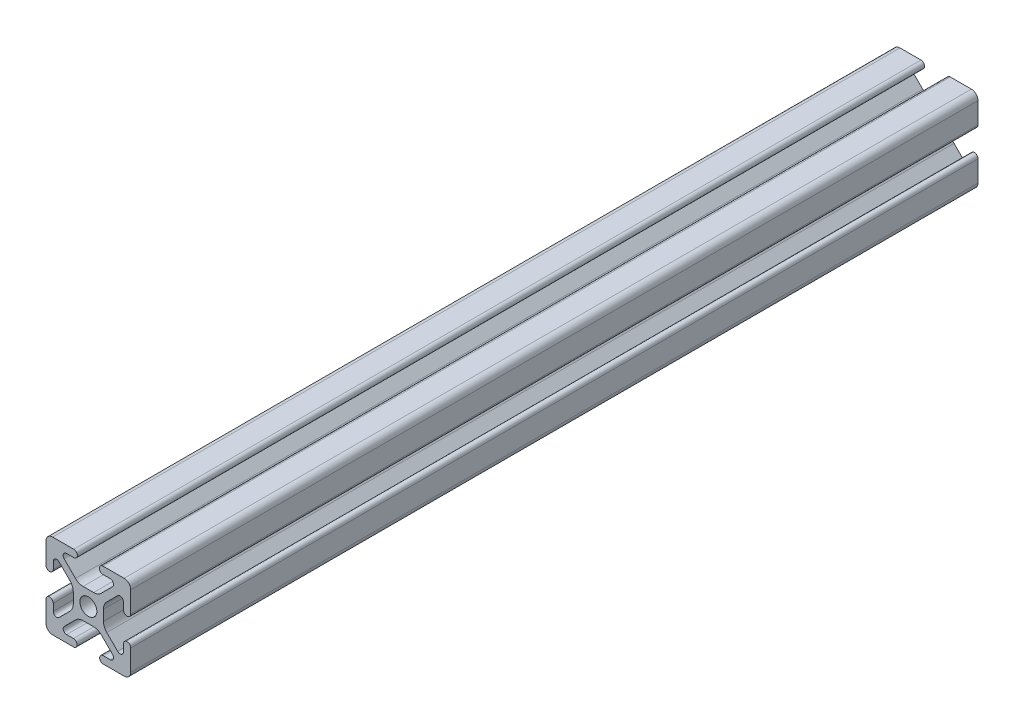
SolidWorks part; units mm, degrees
ref_plane "Front Plane" through (0, 0, 0) normal (0, 0, 1) x (1, 0, 0)
ref_plane "Top Plane" through (0, 0, 0) normal (0, 1, 0) x (1, 0, 0)
ref_plane "Right Plane" through (0, 0, 0) normal (1, 0, 0) x (0, 0, -1)
ref_plane "Plane1" through (0, 0, -25) normal (0, 0, -1) x (-1, 0, 0)
sketch "Sketch1" plane through (0, 0, -25) normal (0, 0, -1) x (-1, 0, 0)
  line L0 (12.5, 4.32) -> (12.5, 10.5371)
  line L1 (10.5371, 12.5) -> (4.32, 12.5)
  line L2 (4.32, 10.36) -> (6.42, 10.36)
  line L3 (7.1337, 8.6353) -> (3.7953, 5.3018)
  line L4 (1.5554, 4.375) -> (-1.5554, 4.375)
  line L5 (-3.7953, 5.3018) -> (-7.1337, 8.6353)
  line L6 (-6.42, 10.36) -> (-4.32, 10.36)
  line L7 (-4.32, 12.5) -> (-10.5371, 12.5)
  line L8 (-12.5, 10.5371) -> (-12.5, 4.32)
  line L9 (-10.36, 4.32) -> (-10.36, 6.3969)
  line L10 (-8.6363, 7.1116) -> (-5.4322, 3.9121)
  line L11 (-4.455, 1.5554) -> (-4.455, -1.5554)
  line L12 (-5.4322, -3.9121) -> (-8.6363, -7.1116)
  line L13 (-10.36, -6.3969) -> (-10.36, -4.32)
  line L14 (-12.5, -4.32) -> (-12.5, -10.5371)
  line L15 (-10.5371, -12.5) -> (-4.3879, -12.5)
  line L16 (-4.3879, -10.36) -> (-6.42, -10.36)
  line L17 (-7.1337, -8.6353) -> (-3.7953, -5.3018)
  line L18 (-1.5554, -4.375) -> (1.5554, -4.375)
  line L19 (3.7953, -5.3018) -> (7.1337, -8.6353)
  line L20 (6.42, -10.36) -> (4.3879, -10.36)
  line L21 (4.3879, -12.5) -> (10.5371, -12.5)
  line L22 (12.5, -10.5371) -> (12.5, -4.32)
  line L23 (10.36, -4.32) -> (10.36, -6.3969)
  line L24 (8.6363, -7.1116) -> (5.4322, -3.9121)
  line L25 (4.455, -1.5554) -> (4.455, 1.5554)
  line L26 (5.4322, 3.9121) -> (8.6363, 7.1116)
  line L27 (10.36, 6.3969) -> (10.36, 4.32)
  circle A0 centre (0, 0) radius 2.5
  arc A1 (12.5, 10.5371) -> (10.5371, 12.5) centre (10.5371, 10.5371) ccw
  arc A2 (4.32, 12.5) -> (4.32, 10.36) centre (4.32, 11.43) ccw
  arc A3 (6.42, 10.36) -> (7.1337, 8.6353) centre (6.42, 9.35) cw
  arc A4 (3.7953, 5.3018) -> (1.5554, 4.375) centre (1.5554, 7.545) cw
  arc A5 (-1.5554, 4.375) -> (-3.7953, 5.3018) centre (-1.5554, 7.545) cw
  arc A6 (-7.1337, 8.6353) -> (-6.42, 10.36) centre (-6.42, 9.35) cw
  arc A7 (-4.32, 10.36) -> (-4.32, 12.5) centre (-4.32, 11.43) ccw
  arc A8 (-10.5371, 12.5) -> (-12.5, 10.5371) centre (-10.5371, 10.5371) ccw
  arc A9 (-12.5, 4.32) -> (-10.36, 4.32) centre (-11.43, 4.32) ccw
  arc A10 (-10.36, 6.3969) -> (-8.6363, 7.1116) centre (-9.35, 6.3969) cw
  arc A11 (-5.4322, 3.9121) -> (-4.455, 1.5554) centre (-7.7855, 1.5554) cw
  arc A12 (-4.455, -1.5554) -> (-5.4322, -3.9121) centre (-7.7855, -1.5554) cw
  arc A13 (-8.6363, -7.1116) -> (-10.36, -6.3969) centre (-9.35, -6.3969) cw
  arc A14 (-10.36, -4.32) -> (-12.5, -4.32) centre (-11.43, -4.32) ccw
  arc A15 (-12.5, -10.5371) -> (-10.5371, -12.5) centre (-10.5371, -10.5371) ccw
  arc A16 (-4.3879, -12.5) -> (-4.3879, -10.36) centre (-4.3879, -11.43) ccw
  arc A17 (-6.42, -10.36) -> (-7.1337, -8.6353) centre (-6.42, -9.35) cw
  arc A18 (-3.7953, -5.3018) -> (-1.5554, -4.375) centre (-1.5554, -7.545) cw
  arc A19 (1.5554, -4.375) -> (3.7953, -5.3018) centre (1.5554, -7.545) cw
  arc A20 (7.1337, -8.6353) -> (6.42, -10.36) centre (6.42, -9.35) cw
  arc A21 (4.3879, -10.36) -> (4.3879, -12.5) centre (4.3879, -11.43) ccw
  arc A22 (10.5371, -12.5) -> (12.5, -10.5371) centre (10.5371, -10.5371) ccw
  arc A23 (12.5, -4.32) -> (10.36, -4.32) centre (11.43, -4.32) ccw
  arc A24 (10.36, -6.3969) -> (8.6363, -7.1116) centre (9.35, -6.3969) cw
  arc A25 (5.4322, -3.9121) -> (4.455, -1.5554) centre (7.7855, -1.5554) cw
  arc A26 (4.455, 1.5554) -> (5.4322, 3.9121) centre (7.7855, 1.5554) cw
  arc A27 (8.6363, 7.1116) -> (10.36, 6.3969) centre (9.35, 6.3969) cw
  arc A28 (10.36, 4.32) -> (12.5, 4.32) centre (11.43, 4.32) ccw
extrude "Boss-Extrude1" add sketch "Sketch1" against normal blind 250
